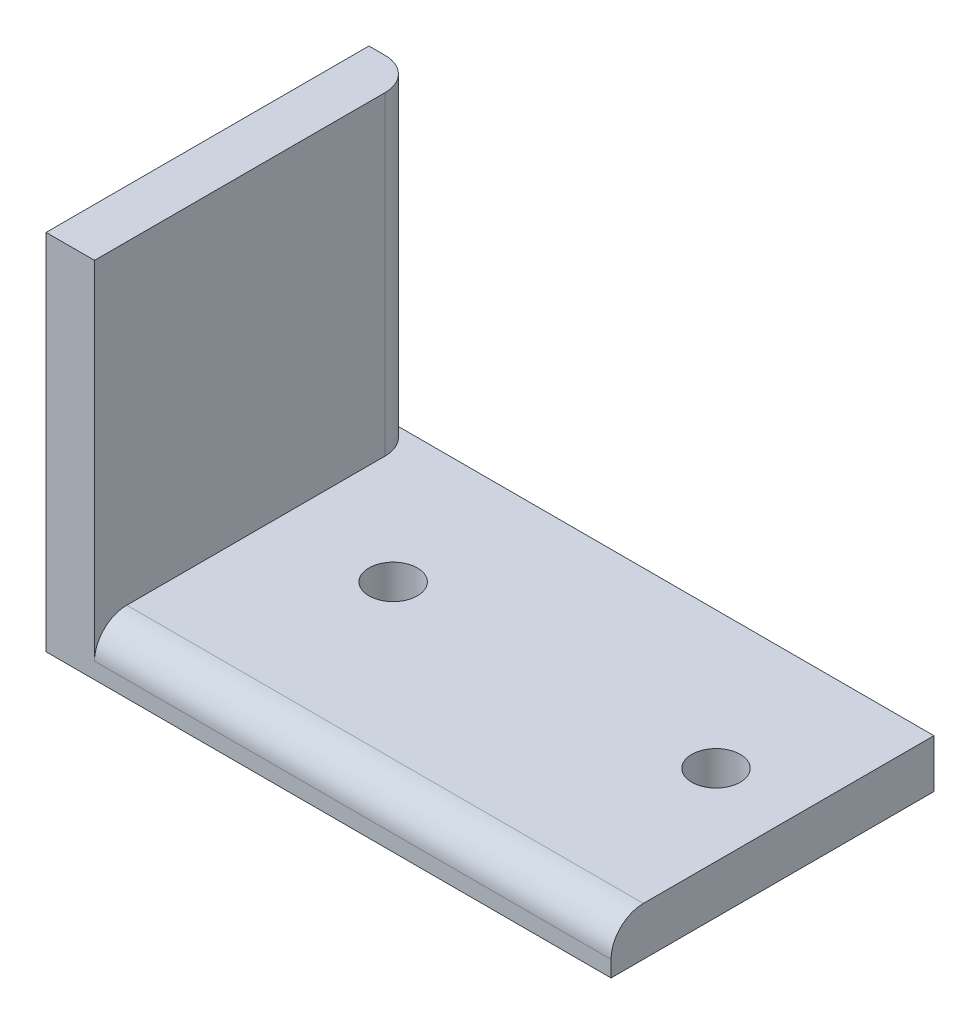
SolidWorks part; units mm, degrees
material "灰铸铁"
ref_plane "前视基准面" through (0, 0, 0) normal (0, 0, 1) x (1, 0, 0)
ref_plane "上视基准面" through (0, 0, 0) normal (0, 1, 0) x (1, 0, 0)
ref_plane "右视基准面" through (0, 0, 0) normal (1, 0, 0) x (0, 0, -1)
other "Configuration Table"
sketch "草图8" plane through (0, 0, 0) normal (0, 0, 1) x (1, 0, 0)
  line L0 (0, 0) -> (140, 0)
  line L1 (140, 0) -> (140, 12)
  line L2 (140, 12) -> (12, 12)
  line L3 (12, 12) -> (12, 90)
  line L4 (12, 90) -> (0, 90)
  line L5 (0, 90) -> (0, 0)
extrude "凸台-拉伸1" add sketch "草图8" along normal mid plane 80
fillet "圆角1" radius 8 2 edges at (76, 12, 40) (12, 51, -40)
sketch "草图9" plane through (0, 0, 0) normal (0, 1, 0) x (1, 0, 0)
  circle A0 centre (40, 6) radius 6
extrude "切除-拉伸7" cut sketch "草图9" along normal through all
sketch "草图10" plane through (0, 0, 0) normal (0, 1, 0) x (1, 0, 0)
  circle A0 centre (120, 6) radius 6
extrude "切除-拉伸14" cut sketch "草图10" along normal through all
